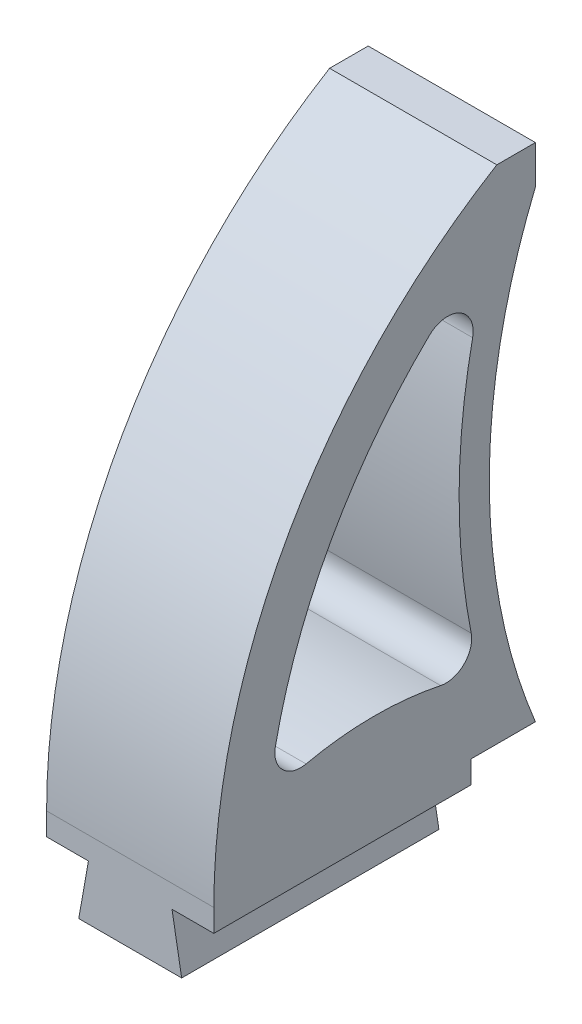
SolidWorks part; units mm, degrees
ref_plane "前视基准面" through (0, 0, 0) normal (0, 0, 1) x (1, 0, 0)
ref_plane "上视基准面" through (0, 0, 0) normal (0, 1, 0) x (1, 0, 0)
ref_plane "右视基准面" through (0, 0, 0) normal (1, 0, 0) x (0, 0, -1)
other "Configuration Table"
sketch "草图1" plane through (0, 0, 0) normal (1, 0, 0) x (0, 0, -1)
  line L0 (0, 0) -> (0, 6)
  line L1 (22, 45) -> (25, 45)
  line L2 (25, 45) -> (25, 42)
  line L3 (25, 6) -> (20, 6)
  line L4 (20, 6) -> (20, 0)
  line L5 (20, 0) -> (0, 0)
  arc A1 (25, 42) -> (25, 6) centre (68.4166, 24) ccw
  arc A2 (22, 45) -> (0, 6) centre (45.5682, 6) ccw
  dimension "D6" = 47
  dimension "D1" = 6
  dimension "D2" = 20
  dimension "D3" = 5
  dimension "D4" = 3
  dimension "D5" = 3
  dimension "D7" = 25
  dimension "D8" = 39
extrude "凸台-拉伸1" add sketch "草图1" along normal mid plane 13
sketch "草图2" plane through (0, 0, 0) normal (0, 0, 1) x (1, 0, 0)
  line L0 (0, 0) -> (0, 22.8846) construction
  line L2 (6.5, 4.2535) -> (6.5, 0)
  line L4 (6.5, 0) -> (4, 0)
  line L13 (6.5, 4.2535) -> (3.25, 4.2535)
  line L14 (6.5, 6) -> (6.5, 0) construction
  line L15 (3.25, 4.2535) -> (4, 0)
  line L16 (6.5, 0) -> (-6.5, 0) construction
  line L17 (-6.5, 4.2535) -> (-6.5, 0)
  line L18 (-6.5, 4.2535) -> (-3.25, 4.2535)
  line L19 (-3.25, 4.2535) -> (-4, 0)
  line L20 (-6.5, 0) -> (-4, 0)
  line M1 (-6.5, 6) -> (-6.5, 0)
  line M2 (-6.5, 0) -> (6.5, 0)
  dimension "D1" = 8
  dimension "D2" = 6.5
  dimension "D3" = 80
extrude "切除-拉伸2" cut sketch "草图2" against normal up to next contours L19 L18 M1 M2 | L4 L15 L13 L2
sketch "草图3" plane through (6.5, 0, 0) normal (1, 0, 0) x (0, 0, -1)
  line L0 (25, 6) -> (0, 6) construction
  line L1 (12.5, 6) -> (12.5, 23.7732) construction
  line L2 (20, 4.2535) -> (0, 4.2535) construction
  arc A0 (7.1697, 12.0791) -> (17.6352, 12.1208) centre (12.5, -12.3461) cw
  arc A1 (20.0085, 14.4638) -> (20.1214, 34.3029) centre (69.0703, 24.1045) cw
  arc A2 (16.7763, 36.1516) -> (4.7851, 14.44) centre (45.9069, 5.8959) ccw
  arc A3 (16.7763, 36.1516) -> (20.1214, 34.3029) centre (18.1635, 34.7108) cw
  arc A4 (7.1697, 12.0791) -> (4.7851, 14.44) centre (6.7433, 14.0331) cw
  arc A5 (20.0085, 14.4638) -> (17.6352, 12.1208) centre (18.0461, 14.0782) cw
  point P17 (21.75, 40.2535)
  point P20 (4.25, 11.2535)
  point P23 (20.75, 11.2535)
  dimension "D1" = 16.5
  dimension "D2" = 25
  dimension "D5" = 42
  dimension "D6" = 50
  dimension "D8" = 2
  dimension "D9" = 2
  dimension "D10" = 2
  dimension "D3" = 29
  dimension "D4" = 17.5
  dimension "D7" = 7
extrude "切除-拉伸3" cut sketch "草图3" against normal up to next
